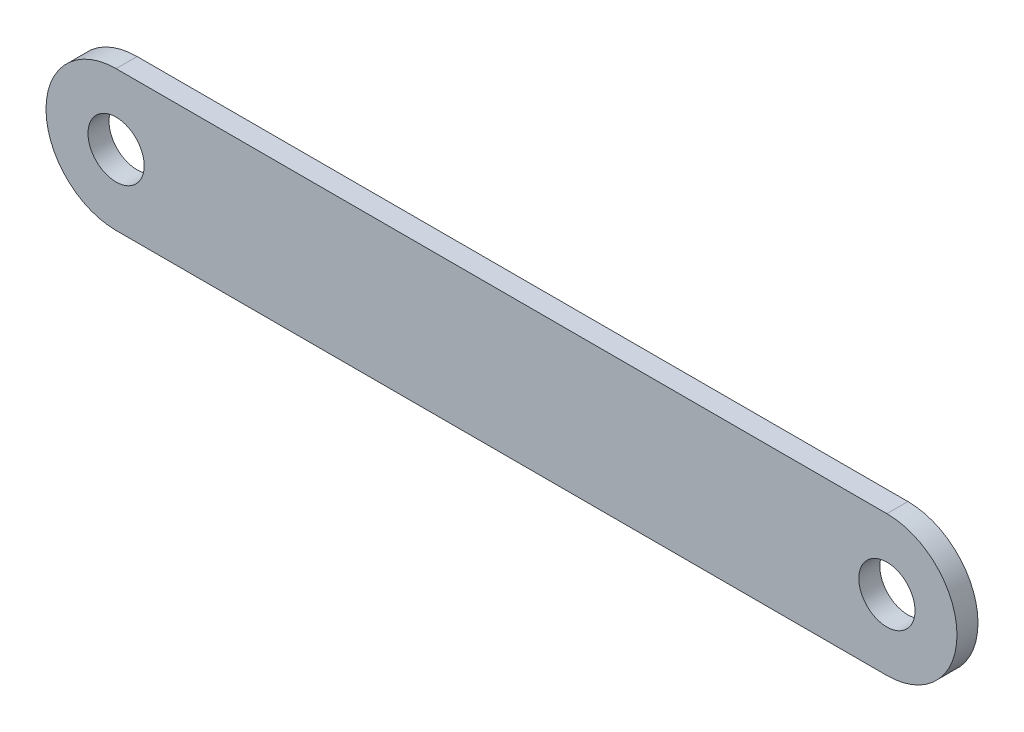
SolidWorks part; units mm, degrees
ref_plane "Front Plane" through (0, 0, 0) normal (0, 0, 1) x (1, 0, 0)
ref_plane "Top Plane" through (0, 0, 0) normal (0, 1, 0) x (1, 0, 0)
ref_plane "Right Plane" through (0, 0, 0) normal (1, 0, 0) x (0, 0, -1)
sketch "Sketch1" plane through (0, 0, 0) normal (0, 0, 1) x (1, 0, 0)
  line L0 (0, 10) -> (110, 10)
  line L1 (0, -10) -> (110, -10)
  circle A0 centre (0, 0) radius 10
  circle A2 centre (0, 0) radius 4.01
  circle A3 centre (110, 0) radius 4.01
  circle A4 centre (110, 0) radius 10
  dimension "D1" = 20
  dimension "D2" = 20
  dimension "D4" = 8.02
  dimension "D5" = 8.02
  dimension "D3" = 110
  dimension "D6" = 110
extrude "Boss-Extrude1" add sketch "Sketch1" along normal blind 3
sketch "Sketch2" plane through (0, 0, 0) normal (0, 0, -1) x (-1, 0, 0)
  circle A2 centre (-20, 0) radius 1.49
  dimension "D1" = 20
  dimension "D2" = 2.98
extrude "Boss-Extrude3" add sketch "Sketch2" along normal blind 4
sketch "Sketch4" plane through (0, 0, 0) normal (0, 0, -1) x (-1, 0, 0)
  line L0 (4.9531, 4.9852) -> (-5.0469, 4.9852)
  line L2 (4.9531, 4.9852) -> (-5.0469, 4.9852)
  line L3 (4.9531, 4.9852) -> (4.9531, 7.4852)
  line L4 (4.9531, 7.4852) -> (-5.0469, 7.4852)
  line L5 (-5.0469, 4.9852) -> (-5.0469, 7.4852)
  dimension "D1" = 2.5
  dimension "D2" = 10
